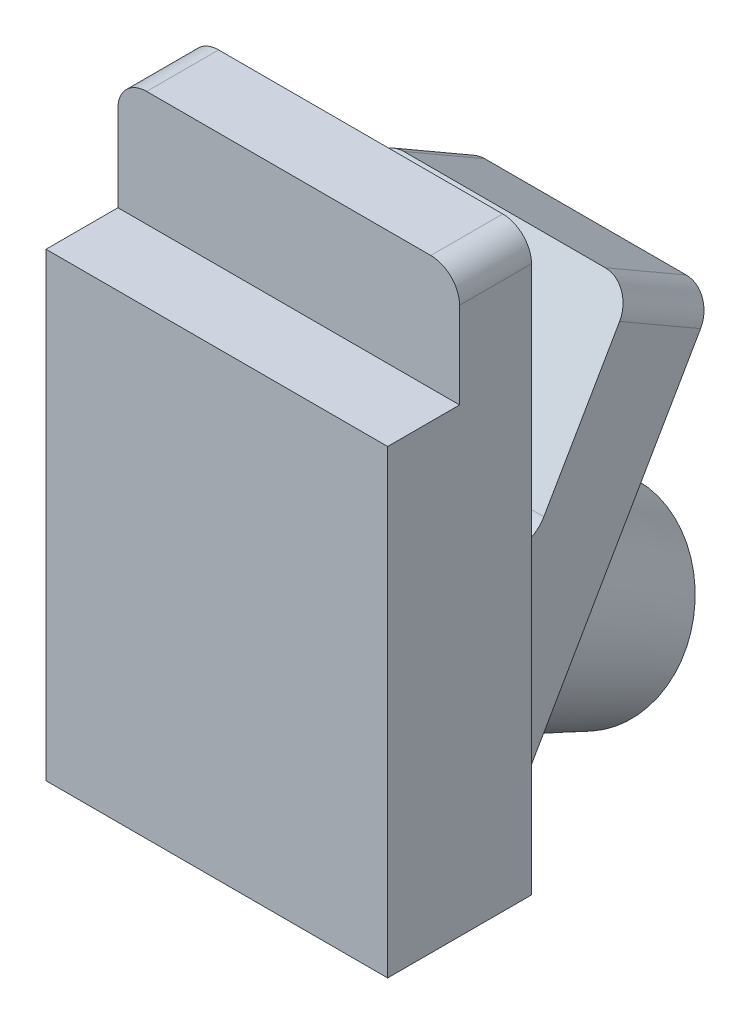
SolidWorks part; units mm, degrees
ref_plane "Ön Düzlem" through (0, 0, 0) normal (0, 0, 1) x (1, 0, 0)
ref_plane "Üst Düzlem" through (0, 0, 0) normal (0, 1, 0) x (1, 0, 0)
ref_plane "Sağ Düzlem" through (0, 0, 0) normal (1, 0, 0) x (0, 0, -1)
sketch "Sketch1" plane through (0, 0, 0) normal (0, 0, 1) x (1, 0, 0)
  line L1 (11.875, 20) -> (-11.875, 20)
  line L2 (11.875, 20) -> (11.875, -20)
  line L3 (11.875, -20) -> (-11.875, -20)
  line L4 (-11.875, 20) -> (-11.875, -20)
  line L5 (11.875, 20) -> (-11.875, -20) construction
  line L6 (11.875, -20) -> (-11.875, 20) construction
  point P0 (0, 0)
  dimension "D1" = 40
  dimension "D2" = 23.75
extrude "Boss-Extrude1" add sketch "Sketch1" against normal blind 10
sketch "Sketch2" plane through (0, 0, 0) normal (0, 0, 1) x (1, 0, 0)
  line L0 (11.875, -20) -> (11.875, 20) construction
  line L1 (-11.875, 20) -> (11.875, 20)
  line L2 (-11.875, 20) -> (-11.875, 12)
  line L3 (-11.875, 12) -> (11.875, 12)
  line L4 (11.875, 20) -> (11.875, 12)
  dimension "D1" = 8
extrude "Cut-Extrude1" cut sketch "Sketch2" against normal blind 5
fillet "Fillet1" radius 2 2 edges at (11.875, 20, -7.5) (-11.875, 20, -7.5)
ref_plane "Plane6" through (0, -9.3301, -16.1603) normal (0, -0.5, -0.866) x (1, 0, 0)
ref_plane "Plane7" through (0, 19.3301, -11.1603) normal (0, -0.866, 0.5) x (-1, 0, 0)
sketch "Sketch6" plane through (0, 19.3301, -11.1603) normal (0, -0.866, 0.5) x (-1, 0, 0)
  line L0 (0, 0) -> (0, 26.2444) construction
  line L1 (13.0625, 18.6603) -> (-13.0625, 18.6603) construction
  line L2 (9, 18.6603) -> (-9, 18.6603)
  line L3 (9, 18.6603) -> (9, 12.1603)
  line L4 (9, 12.1603) -> (-9, 12.1603)
  line L5 (-9, 18.6603) -> (-9, 12.1603)
  dimension "D1" = 18
  dimension "D2" = 6.5
extrude "Boss-Extrude3" add sketch "Sketch6" along normal up to surface (34.641 mm away)
sketch "Sketch7" plane through (0, 19.3301, -11.1603) normal (0, 0.866, -0.5) x (1, 0, 0)
  line L4 (-9, 18.6603) -> (-9, 12.1603)
  line L5 (-9, 12.1603) -> (9, 12.1603)
  line L6 (9, 12.1603) -> (9, 18.6603)
  line L7 (9, 18.6603) -> (-9, 18.6603)
  line L8 (-9, 18.6603) -> (-9, 12.1603)
  line L9 (-9, 12.1603) -> (9, 12.1603)
  line L10 (9, 12.1603) -> (9, 18.6603)
  line L11 (9, 18.6603) -> (-9, 18.6603)
  dimension "D1" = 0
extrude "Cut-Extrude2" cut sketch "Sketch7" against normal blind 3.38
fillet "Fillet4" radius 2 3 edges at (0, -7, -10) (9, 8.6978, -22.8159) (-9, 8.6978, -22.8159)
sketch "Sketch8" plane through (0, -9.3301, -16.1603) normal (0, -0.5, -0.866) x (-1, 0, 0)
  line L0 (-9, -12.3205) -> (9, -12.3205) construction
  circle A0 centre (0, -1.0205) radius 7.5
  dimension "D2" = 15
  dimension "D1" = 11.3
extrude "Boss-Extrude4" add sketch "Sketch8" along normal blind 12 draft 5
sketch "Sketch9" plane through (0, -15.3301, -26.5526) normal (0, -0.5, -0.866) x (-1, 0, 0)
  circle A0 centre (0, -1.0205) radius 5
  dimension "D1" = 10
extrude "Cut-Extrude4" cut sketch "Sketch9" against normal blind 12
sketch "Sketch10" plane through (0, -9.3301, -16.1603) normal (0, -0.5, -0.866) x (-1, 0, 0)
  circle A1 centre (0, -1.0205) radius 5
  circle A2 centre (0, -1.0205) radius 5
  dimension "D1" = 0
extrude "Cut-Extrude5" cut sketch "Sketch10" along normal blind 12 draft 5 draft outward yes
